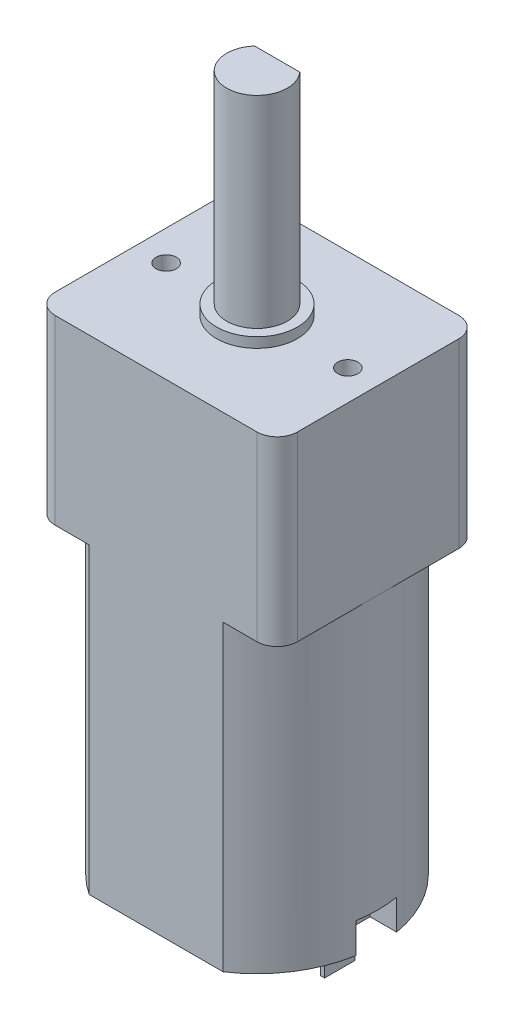
SolidWorks part; units mm, degrees
ref_plane "Front Plane" through (0, 0, 0) normal (0, 0, 1) x (1, 0, 0)
ref_plane "Top Plane" through (0, 0, 0) normal (0, 1, 0) x (1, 0, 0)
ref_plane "Right Plane" through (0, 0, 0) normal (1, 0, 0) x (0, 0, -1)
sketch "Sketch1" plane through (0, 0, 0) normal (0, 1, 0) x (1, 0, 0)
  line L0 (-3.3166, 5) -> (3.3166, 5)
  line L1 (-3.3166, -5) -> (3.3166, -5)
  arc A0 (-3.3166, 5) -> (-3.3166, -5) centre (0, 0) ccw
  arc A1 (3.3166, -5) -> (3.3166, 5) centre (0, 0) ccw
  dimension "D1" = 12
  dimension "D2" = 10
extrude "Boss-Extrude1" add sketch "Sketch1" along normal blind 15
sketch "Sketch2" plane through (0, 0, 0) normal (0, -1, 0) x (1, 0, 0)
  circle A0 centre (0, 0) radius 2.5
  dimension "D1" = 5
extrude "Boss-Extrude2" add sketch "Sketch2" along normal blind 1.2
sketch "Sketch3" plane through (0, 0, 0) normal (0, -1, 0) x (1, 0, 0)
  line L0 (0, 5) -> (0, -5) construction
  line L1 (-3.3166, 5) -> (3.3166, 5) construction
  line L2 (3.3166, -5) -> (-3.3166, -5) construction
  line L3 (4.1, -0.75) -> (3.9, -0.75)
  line L4 (-4.1, 0.75) -> (-3.9, 0.75)
  line L5 (-4.1, 0.75) -> (-4.1, -0.75)
  line L6 (-4.1, -0.75) -> (-3.9, -0.75)
  line L7 (-3.9, 0.75) -> (-3.9, -0.75)
  line L8 (3.9, 0.75) -> (3.9, -0.75)
  line L9 (4.1, 0.75) -> (3.9, 0.75)
  line L10 (4.1, 0.75) -> (4.1, -0.75)
  point P10 (-3.9, 0)
  point P15 (-4, -0.75)
  point P17 (4, -0.75)
  dimension "D1" = 1.5
  dimension "D2" = 0.2
  dimension "D3" = 8
extrude "Boss-Extrude3" add sketch "Sketch3" along normal blind 2
sketch "Sketch4" plane through (0, 0, 0) normal (0, -1, 0) x (1, 0, 0)
  line L0 (0, 5) -> (0, -5) construction
  line L1 (-6, 1) -> (-4.6, 1)
  line L2 (-6, 1) -> (-6, -1)
  line L3 (-6, -1) -> (-4.6, -1)
  line L4 (-4.6, 1) -> (-4.6, -1)
  line L5 (-3.3166, 5) -> (3.3166, 5) construction
  line L6 (3.3166, -5) -> (-3.3166, -5) construction
  line L7 (6, -1) -> (4.6, -1)
  line L8 (4.6, 1) -> (4.6, -1)
  line L9 (6, 1) -> (4.6, 1)
  line L10 (6, 1) -> (6, -1)
  arc A0 (-3.3166, 5) -> (-3.3166, -5) centre (0, 0) ccw construction
  point P13 (-6, 0)
  point P14 (-4.6, 0)
  dimension "D1" = 1.4
  dimension "D2" = 2
extrude "Cut-Extrude1" cut sketch "Sketch4" against normal blind 1.5
sketch "Sketch5" plane through (0, 15, 0) normal (0, 1, 0) x (1, 0, 0)
  line L0 (3.3166, 5) -> (-3.3166, 5) construction
  line L1 (-5, 5) -> (5, 5)
  line L2 (-6, 4) -> (-6, -4)
  line L3 (-5, -5) -> (5, -5)
  line L4 (6, 4) -> (6, -4)
  line L5 (-3.3166, -5) -> (3.3166, -5) construction
  arc A0 (3.3166, -5) -> (3.3166, 5) centre (0, 0) ccw construction
  arc A1 (-3.3166, 5) -> (-3.3166, -5) centre (0, 0) ccw construction
  arc A2 (5, 5) -> (6, 4) centre (5, 4) cw
  arc A3 (5, -5) -> (6, -4) centre (5, -4) ccw
  arc A4 (-6, -4) -> (-5, -5) centre (-5, -4) ccw
  arc A5 (-5, 5) -> (-6, 4) centre (-5, 4) ccw
  dimension "D1" = 1
extrude "Boss-Extrude4" add sketch "Sketch5" along normal blind 9
sketch "Sketch6" plane through (0, 24, 0) normal (0, 1, 0) x (1, 0, 0)
  line L0 (-1.118, 1) -> (1.118, 1)
  line L1 (-5, -5) -> (5, -5) construction
  arc A0 (-1.118, 1) -> (1.118, 1) centre (0, 0) ccw
  dimension "D1" = 3
  dimension "D2" = 1
extrude "Boss-Extrude5" add sketch "Sketch6" along normal blind 10.5
sketch "Sketch7" plane through (0, 24, 0) normal (0, 1, 0) x (1, 0, 0)
  circle A0 centre (0, 0) radius 2
  dimension "D1" = 4
extrude "Boss-Extrude6" add sketch "Sketch7" along normal blind 0.5
sketch "Sketch8" plane through (0, 24, 0) normal (0, 1, 0) x (1, 0, 0)
  line L0 (0, 5) -> (0, -5) construction
  line L1 (5, 5) -> (-5, 5) construction
  line L2 (-5, -5) -> (5, -5) construction
  circle A0 centre (-4.5, 0) radius 0.5
  circle A1 centre (4.5, 0) radius 0.5
  dimension "D1" = 1
  dimension "D2" = 9
extrude "Cut-Extrude2" cut sketch "Sketch8" against normal blind 4.5
sketch "Sketch9" plane through (0, 0, 0) normal (0, -1, 0) x (1, 0, 0)
  line L8 (-4.6, -1) -> (-5.9161, -1)
  line L9 (-3.3166, -5) -> (3.3166, -5)
  line L10 (5.9161, -1) -> (4.6, -1)
  line L11 (4.6, -1) -> (4.6, 1)
  line L12 (4.6, 1) -> (5.9161, 1)
  line L13 (3.3166, 5) -> (-3.3166, 5)
  line L14 (-5.9161, 1) -> (-4.6, 1)
  line L15 (-4.6, 1) -> (-4.6, -1)
  line L16 (-4.6, -1) -> (-5.9161, -1)
  line L17 (-3.3166, -5) -> (3.3166, -5)
  line L18 (5.9161, -1) -> (4.6, -1)
  line L19 (4.6, -1) -> (4.6, 1)
  line L20 (4.6, 1) -> (5.9161, 1)
  line L21 (3.3166, 5) -> (-3.3166, 5)
  line L22 (-5.9161, 1) -> (-4.6, 1)
  line L23 (-4.6, 1) -> (-4.6, -1)
  circle A1 centre (0, 0) radius 2.5
  circle A2 centre (0, 0) radius 2.5
  arc A4 (-5.9161, -1) -> (-3.3166, -5) centre (0, 0) ccw
  arc A5 (3.3166, -5) -> (5.9161, -1) centre (0, 0) ccw
  arc A6 (5.9161, 1) -> (3.3166, 5) centre (0, 0) ccw
  arc A7 (-3.3166, 5) -> (-5.9161, 1) centre (0, 0) ccw
  arc A8 (-5.9161, -1) -> (-3.3166, -5) centre (0, 0) ccw
  arc A9 (3.3166, -5) -> (5.9161, -1) centre (0, 0) ccw
  arc A10 (5.9161, 1) -> (3.3166, 5) centre (0, 0) ccw
  arc A11 (-3.3166, 5) -> (-5.9161, 1) centre (0, 0) ccw
  dimension "D1" = 0
  dimension "D2" = 0
